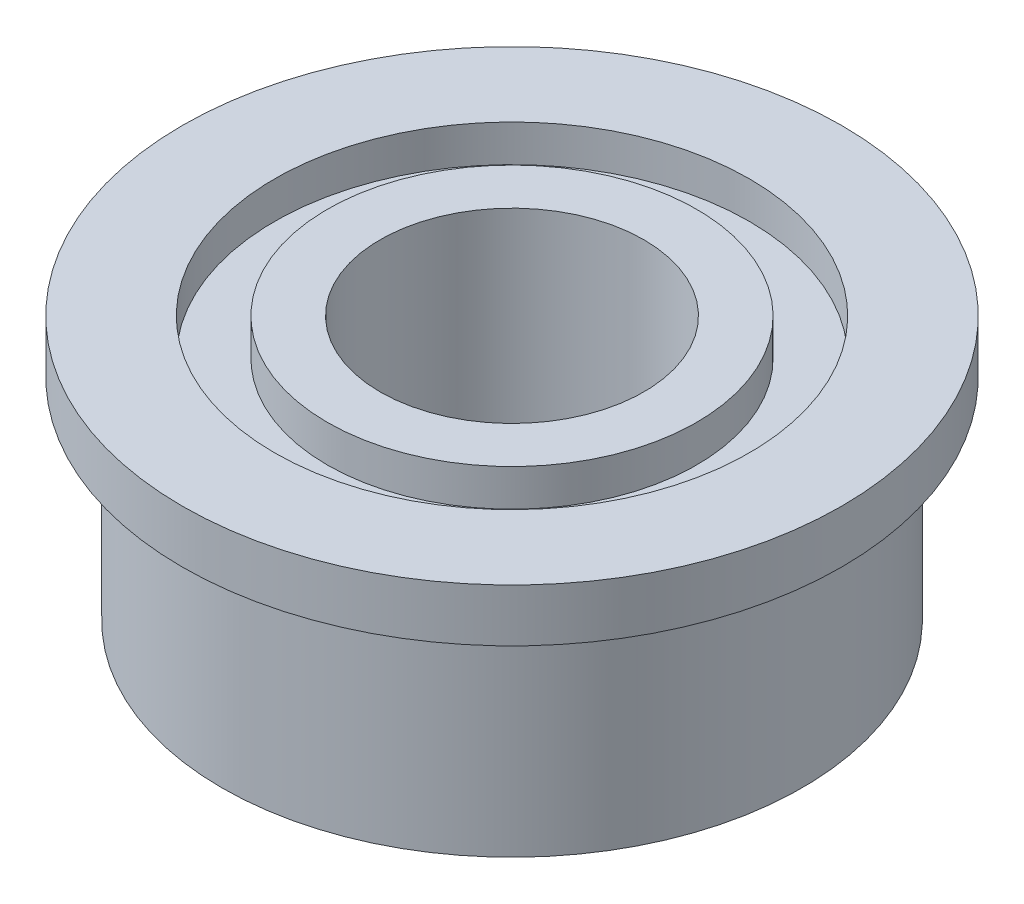
SolidWorks part; units mm, degrees
ref_plane "前视基准面" through (0, 0, 0) normal (0, 0, 1) x (1, 0, 0)
ref_plane "上视基准面" through (0, 0, 0) normal (0, 1, 0) x (1, 0, 0)
ref_plane "右视基准面" through (0, 0, 0) normal (1, 0, 0) x (0, 0, -1)
other "Configuration Table"
sketch "草图1" plane through (0, 0, 0) normal (0, 0, 1) x (1, 0, 0)
  line L0 (0, 4.6113) -> (0, -3.0029) construction
  line L1 (2.5, 5) -> (2.5, 0)
  line L2 (2.5, 0) -> (3.5, 0)
  line L3 (3.5, 0) -> (3.5, 0.7)
  line L4 (3.5, 0.7) -> (4.5, 0.7)
  line L5 (4.5, 0.7) -> (4.5, 0)
  line L6 (4.5, 0) -> (5.5, 0)
  line L7 (5.5, 0) -> (5.5, 5)
  line L8 (5.5, 5) -> (4.5, 5)
  line L9 (4.5, 5) -> (4.5, 4.3)
  line L10 (4.5, 4.3) -> (3.5, 4.3)
  line L11 (3.5, 4.3) -> (3.5, 5)
  line L12 (3.5, 5) -> (2.5, 5)
  dimension "D1" = 2.5
  dimension "D2" = 5.5
  dimension "D3" = 5
  dimension "D4" = 1
  dimension "D5" = 1
  dimension "D6" = 0.7
  dimension "D7" = 0.7
revolve "旋转1" add sketch "草图1" angle 360 about L0
fillet "圆角1" [suppressed] radius 0.2
sketch "草图2" plane through (0, 5, 0) normal (0, 1, 0) x (1, 0, 0)
  circle A0 centre (0, 0) radius 5.5
  circle A1 centre (0, 0) radius 6.25
  dimension "D1" = 12.5
extrude "凸台-拉伸1" add sketch "草图2" against normal blind 1
